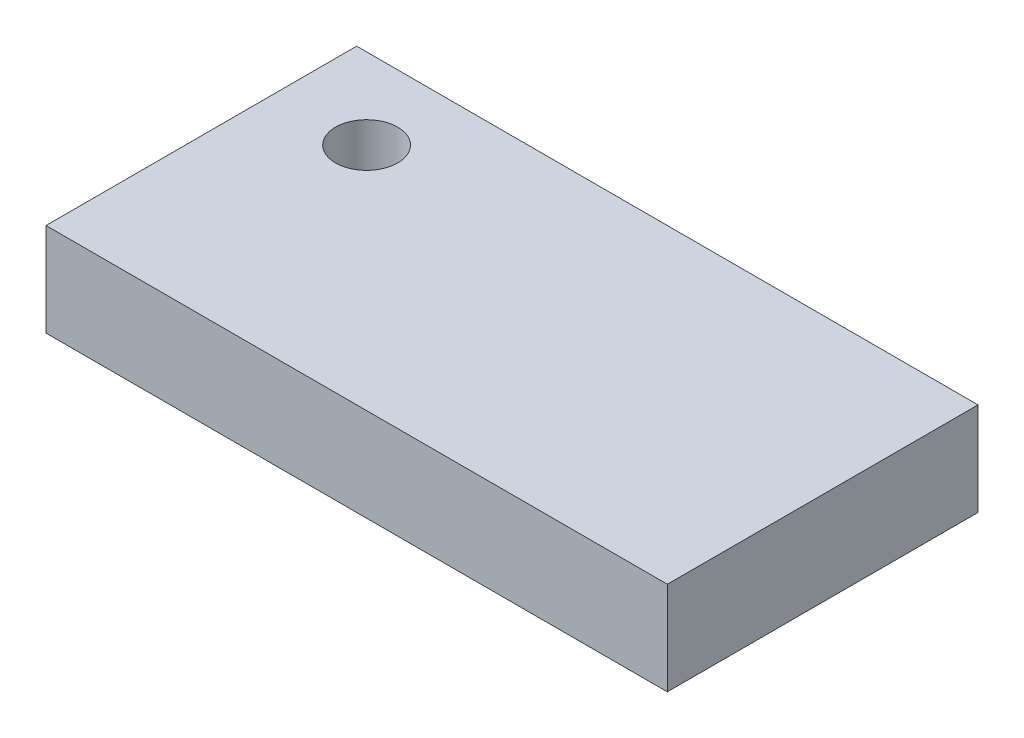
SolidWorks part; units mm, degrees
ref_plane "Front Plane" through (0, 0, 0) normal (0, 0, 1) x (1, 0, 0)
ref_plane "Top Plane" through (0, 0, 0) normal (0, 1, 0) x (1, 0, 0)
ref_plane "Right Plane" through (0, 0, 0) normal (1, 0, 0) x (0, 0, -1)
sketch "Sketch1" plane through (0, 0, 0) normal (0, 1, 0) x (1, 0, 0)
  line L1 (-50, -16.3344) -> (50, -16.3344)
  line L2 (-50, -16.3344) -> (-50, 33.6656)
  line L3 (-50, 33.6656) -> (50, 33.6656)
  line L4 (50, -16.3344) -> (50, 33.6656)
  line L5 (-50, -16.3344) -> (50, 33.6656) construction
  line L6 (-50, 33.6656) -> (50, -16.3344) construction
  point P0 (0, 8.6656)
  dimension "D1" = 100
  dimension "D2" = 50
extrude "Boss-Extrude1" add sketch "Sketch1" along normal blind 15
sketch "Sketch2" plane through (0, 15, 0) normal (0, 1, 0) x (1, 0, 0)
  circle A0 centre (-35.4172, 20.6809) radius 5
  dimension "D1" = 10
extrude "Cut-Extrude1" cut sketch "Sketch2" against normal blind 10
